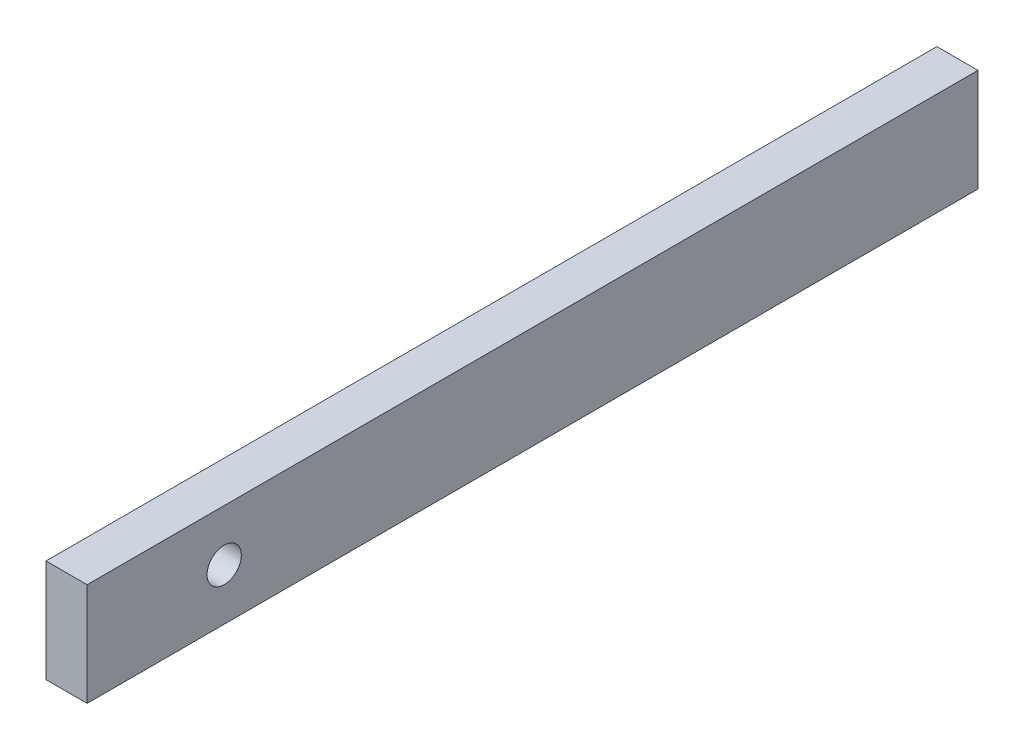
SolidWorks part; units mm, degrees
ref_plane "Plan de face" through (0, 0, 0) normal (0, 0, 1) x (1, 0, 0)
ref_plane "Plan de dessus" through (0, 0, 0) normal (0, 1, 0) x (1, 0, 0)
ref_plane "Plan de droite" through (0, 0, 0) normal (1, 0, 0) x (0, 0, -1)
sketch "Esquisse1" plane through (0, 0, 0) normal (0, 0, 1) x (1, 0, 0)
  line L1 (-3, 7.5) -> (3, 7.5)
  line L2 (-3, 7.5) -> (-3, -7.5)
  line L3 (-3, -7.5) -> (3, -7.5)
  line L4 (3, 7.5) -> (3, -7.5)
  line L5 (-3, 7.5) -> (3, -7.5) construction
  line L6 (-3, -7.5) -> (3, 7.5) construction
  point P0 (0, 0)
  dimension "D1" = 6
  dimension "D2" = 15
extrude "Boss.-Extru.1" add sketch "Esquisse1" along normal blind 170
sketch "Esquisse2" plane through (3, 0, 0) normal (1, 0, 0) x (0, 0, -1)
  line L0 (-170, -7.5) -> (-170, 7.5) construction
  line L1 (-170, -7.5) -> (0, -7.5) construction
  circle A0 centre (-150, 0) radius 2.5
  dimension "D1" = 5
  dimension "D2" = 20
  dimension "D3" = 7.5
extrude "Enlèv. mat.-Extru.1" cut sketch "Esquisse2" against normal blind 10
sketch "Sketch1" plane through (0, 0, 0) normal (0, 0, -1) x (-1, 0, 0)
  line L4 (-3, 7.5) -> (-3, -7.5)
  line L5 (-3, -7.5) -> (3, -7.5)
  line L6 (3, -7.5) -> (3, 7.5)
  line L7 (3, 7.5) -> (-3, 7.5)
  line L8 (-3, 7.5) -> (-3, -7.5)
  line L9 (-3, -7.5) -> (3, -7.5)
  line L10 (3, -7.5) -> (3, 7.5)
  line L11 (3, 7.5) -> (-3, 7.5)
  dimension "D1" = 0
extrude "Cut-Extrude1" cut sketch "Sketch1" against normal blind 40
